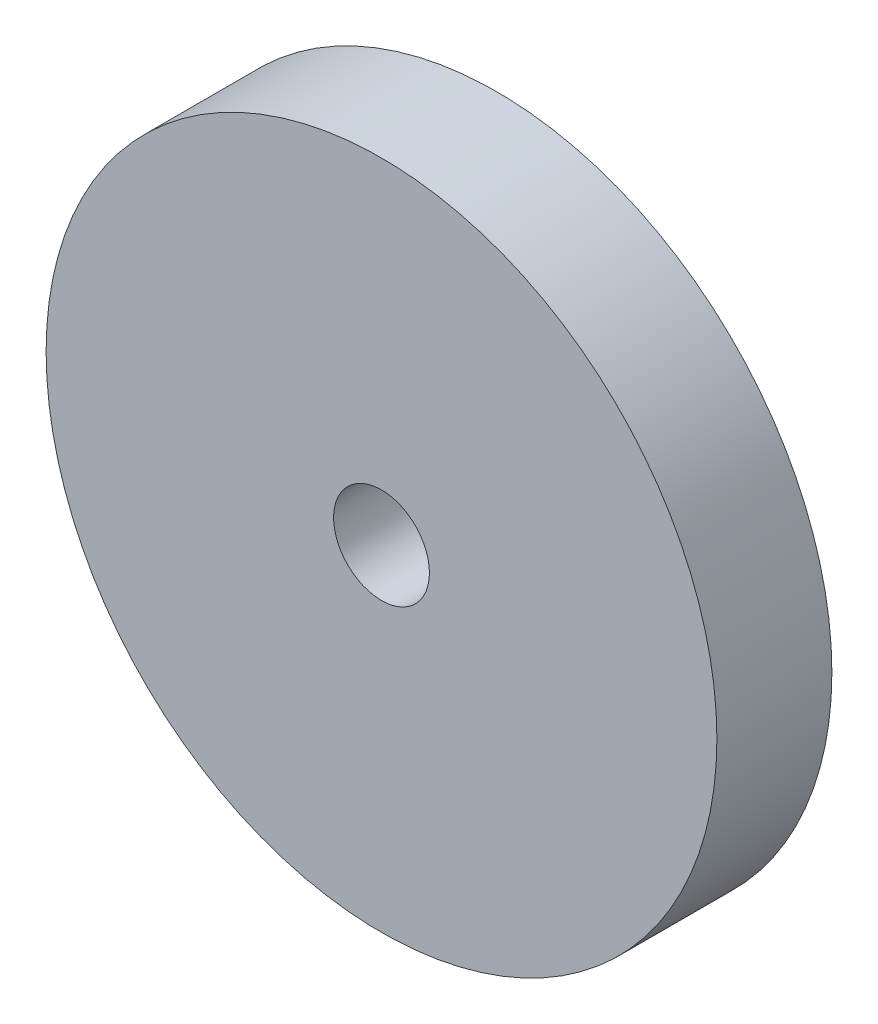
SolidWorks part; units mm, degrees
ref_plane "前基準面" through (0, 0, 0) normal (0, 0, 1) x (1, 0, 0)
ref_plane "上基準面" through (0, 0, 0) normal (0, 1, 0) x (1, 0, 0)
ref_plane "右基準面" through (0, 0, 0) normal (1, 0, 0) x (0, 0, -1)
sketch "草圖1" plane through (0, 0, 0) normal (0, 0, 1) x (1, 0, 0)
  circle A0 centre (0, 0) radius 8.75
  circle A1 centre (0, 0) radius 1.25
  dimension "D1" = 2.5
  dimension "D2" = 17.5
extrude "填料-伸長1" add sketch "草圖1" along normal blind 3
